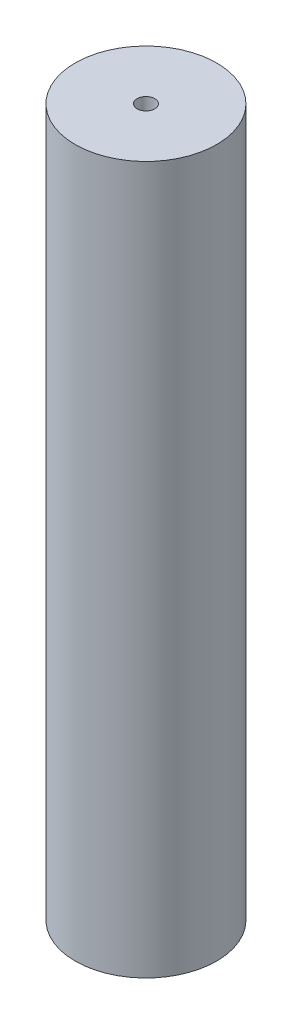
SolidWorks part; units mm, degrees
material "普通碳钢"
ref_plane "前视基准面" through (0, 0, 0) normal (0, 0, 1) x (1, 0, 0)
ref_plane "上视基准面" through (0, 0, 0) normal (0, 1, 0) x (1, 0, 0)
ref_plane "右视基准面" through (0, 0, 0) normal (1, 0, 0) x (0, 0, -1)
sketch "草图1" plane through (0, 0, 0) normal (0, 1, 0) x (1, 0, 0)
  circle A0 centre (0, 0) radius 20
  dimension "D1" = 40
extrude "凸台-拉伸1" add sketch "草图1" along normal blind 200
sketch "草图2" plane through (0, 200, 0) normal (0, 1, 0) x (1, 0, 0)
  circle A0 centre (0, 0) radius 2.5
  dimension "D1" = 5
extrude "切除-拉伸1" cut sketch "草图2" against normal blind 22
